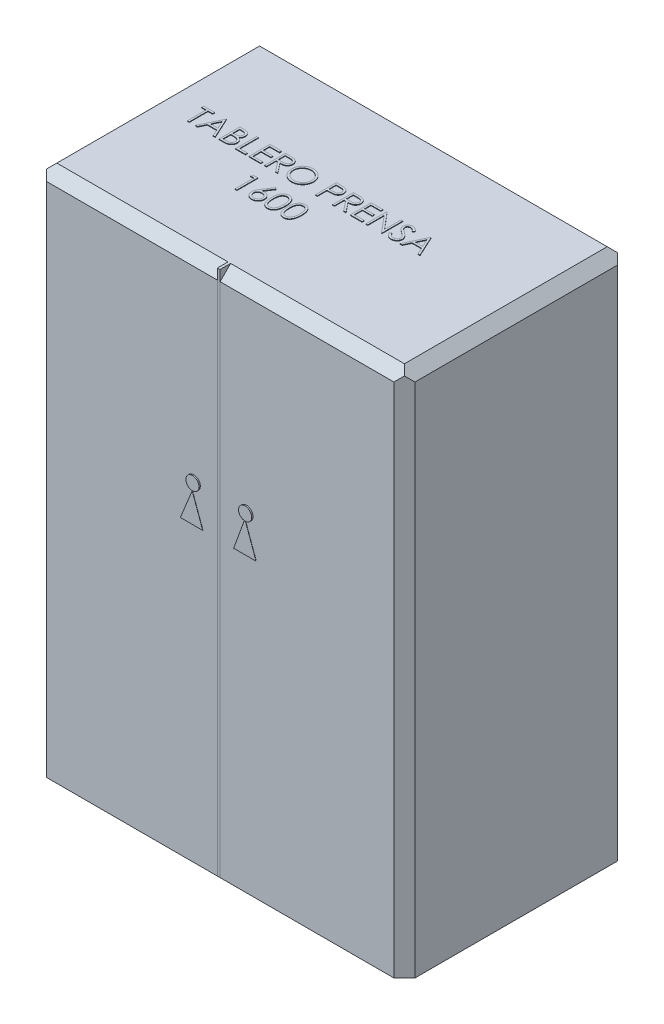
SolidWorks part; units mm, degrees
ref_plane "Alzado" through (0, 0, 0) normal (0, 0, 1) x (1, 0, 0)
ref_plane "Planta" through (0, 0, 0) normal (0, 1, 0) x (1, 0, 0)
ref_plane "Vista lateral" through (0, 0, 0) normal (1, 0, 0) x (0, 0, -1)
sketch "Croquis1" plane through (0, 0, 0) normal (0, 1, 0) x (1, 0, 0)
  line L1 (-700, 425) -> (700, 425)
  line L2 (-700, 425) -> (-700, -425)
  line L3 (-700, -425) -> (700, -425)
  line L4 (700, 425) -> (700, -425)
  line L5 (-700, 425) -> (700, -425) construction
  line L6 (-700, -425) -> (700, 425) construction
  point P0 (0, 0)
  dimension "D1" = 1400
  dimension "D2" = 850
extrude "Saliente-Extruir1" add sketch "Croquis1" along normal blind 2000
sketch "Croquis2" plane through (0, 0, 425) normal (0, 0, 1) x (1, 0, 0)
  line L0 (0, 2000) -> (0, 0)
  line L1 (-700, 2000) -> (700, 2000) construction
  line L2 (0, 1000) -> (700, 1000) construction
  line L3 (700, 2000) -> (700, 0) construction
  line L4 (-700, 1000) -> (0, 1000) construction
  line L5 (-700, 2000) -> (-700, 0) construction
  line L6 (-700, 1250) -> (700, 1250) construction
  circle A0 centre (-100, 1250) radius 25
  circle A1 centre (100, 1250) radius 25
  dimension "D2" = 50
  dimension "D4" = 50
  dimension "D1" = 250
  dimension "D3" = 1400
  dimension "D5" = 100
  dimension "D6" = 100
extrude "Saliente-Extruir2" add sketch "Croquis2" along normal blind 5 contours A1 | A0
sketch "Croquis3" plane through (0, 0, 425) normal (0, 0, 1) x (1, 0, 0)
  line L0 (0, 2000) -> (0, 0)
  line L1 (-700, 2000) -> (700, 2000) construction
extrude "Extruir-Lámina1" add sketch "Croquis3" along normal blind 0.1 thin
sketch "Croquis4" plane through (0, 0, 430) normal (0, 0, 1) x (1, 0, 0)
  line L0 (97.5367, 1225.1217) -> (57.5, 1115.1217)
  line L1 (102.4633, 1225.1217) -> (142.5, 1115.1217)
  line L2 (57.5, 1115.1217) -> (142.5, 1115.1217)
  circle A0 centre (100, 1250) radius 25 construction
  circle A2 centre (100, 1250) radius 25
  arc A3 (97.5367, 1225.1217) -> (102.4633, 1225.1217) centre (100, 1250) ccw
  dimension "D1" = 110
  dimension "D2" = 110
  dimension "D3" = 85
  dimension "D4" = 290
  dimension "D5" = 290
  dimension "D6" = 0
extrude "Saliente-Extruir3" add sketch "Croquis4" along normal blind 1 separate body
sketch "Croquis5" plane through (0, 0, 430) normal (0, 0, 1) x (1, 0, 0)
  line L0 (-100, 1225) -> (-144.9633, 1115)
  line L1 (-144.9633, 1115) -> (-59.9633, 1115)
  line L4 (-100, 1225) -> (-59.9633, 1115)
  circle A2 centre (-100, 1250) radius 25 construction
  circle A3 centre (-100, 1250) radius 25 construction
  dimension "D1" = 110
  dimension "D2" = 110
  dimension "D3" = 85
  dimension "D4" = 290
  dimension "D5" = 292.233
extrude "Saliente-Extruir4" add sketch "Croquis5" along normal blind 1 separate body
chamfer "Chaflán6" distance 40 angle 45 1 edges at (-700, 2000, 0)
chamfer "Chaflán7" distance 40 angle 45 1 edges at (700, 2000, 0)
chamfer "Chaflán8" distance 40 angle 45 1 edges at (330, 2000, 425)
chamfer "Chaflán9" distance 40 angle 45 1 edges at (-335, 2000, 425)
chamfer "Chaflán10" distance 40 angle 45 1 edges at (0, 2000, -425)
chamfer "Chaflán11" distance 40 angle 45 1 edges at (-700, 980, 425)
chamfer "Chaflán12" distance 40 angle 45 1 edges at (700, 980, 425)
chamfer "Chaflán13" distance 40 angle 45 1 edges at (700, 980, -425)
chamfer "Chaflán14" distance 40 angle 45 1 edges at (-700, 980, -425)
sketch "Croquis6" plane through (0, 2000, 0) normal (0, 1, 0) x (1, 0, 0)
  line L0 (-567.5133, 0) -> (613.0101, 0) construction
  text T0 "TABLERO PRENSA\r\n          1600" font "Century Gothic" height in points 300
extrude "Saliente-Extruir5" add sketch "Croquis6" along normal blind 2
sketch "Croquis7" plane through (0, 0, -425) normal (0, 0, -1) x (-1, 0, 0)
  line L0 (-660, 0) -> (660, 0) construction
  line L1 (-5.2729, 1960) -> (7.6326, 1960)
  line L2 (-5.2729, 1960) -> (-5.2729, 0)
  line L3 (-5.2729, 0) -> (7.6326, 0)
  line L4 (7.6326, 1960) -> (7.6326, 0)
  line L5 (-5.2729, 1960) -> (7.6326, 0) construction
  line L6 (-5.2729, 0) -> (7.6326, 1960) construction
  line L7 (660, 1960) -> (-660, 1960) construction
  point P0 (1.1799, 980)
  point P7 (7.6326, 1960)
extrude "Cortar-Extruir1" cut sketch "Croquis7" against normal blind 1
sketch "Croquis8" plane through (0, 0, -425) normal (0, 0, -1) x (-1, 0, 0)
  circle A0 centre (-139.177, 935.629) radius 25.3049
  circle A1 centre (118.0896, 935.629) radius 25.3049
extrude "Cortar-Extruir2" cut sketch "Croquis8" against normal blind 2
